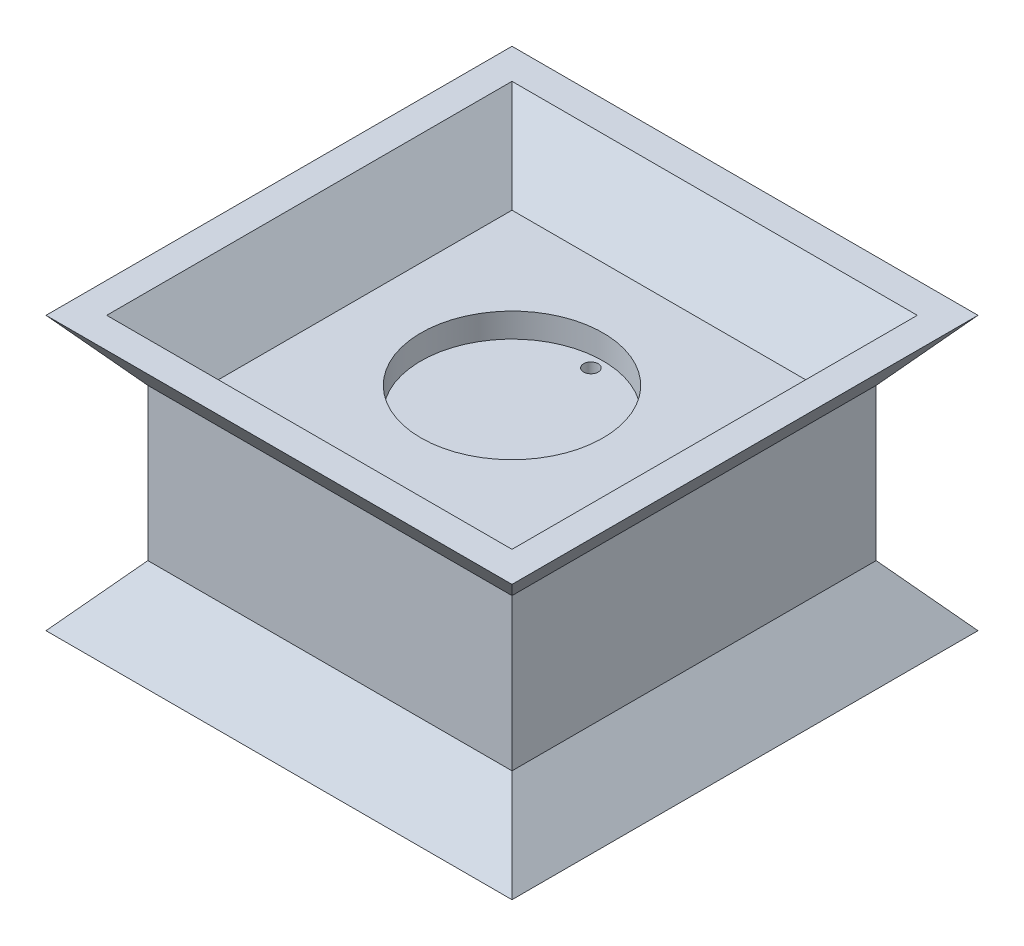
SolidWorks part; units mm, degrees
ref_plane "Front Plane" through (0, 0, 0) normal (0, 0, 1) x (1, 0, 0)
ref_plane "Top Plane" through (0, 0, 0) normal (0, 1, 0) x (1, 0, 0)
ref_plane "Right Plane" through (0, 0, 0) normal (1, 0, 0) x (0, 0, -1)
sketch "Sketch1" plane through (0, 0, 0) normal (0, 1, 0) x (1, 0, 0)
  line L1 (-38.1, -38.1) -> (38.1, -38.1)
  line L2 (-38.1, -38.1) -> (-38.1, 38.1)
  line L3 (-38.1, 38.1) -> (38.1, 38.1)
  line L4 (38.1, -38.1) -> (38.1, 38.1)
  line L5 (-38.1, -38.1) -> (38.1, 38.1) construction
  line L6 (-38.1, 38.1) -> (38.1, -38.1) construction
  point P0 (0, 0)
  dimension "D1" = 76.2
extrude "Boss-Extrude1" add sketch "Sketch1" along normal mid plane 31.75
sketch "Sketch2" plane through (0, 15.875, 0) normal (0, 1, 0) x (1, 0, 0)
  line L0 (-38.1, -38.1) -> (38.1, -38.1) construction
  line L1 (-38.1, 38.1) -> (38.1, 38.1)
  line L2 (-38.1, 38.1) -> (-38.1, -38.1)
  line L3 (-38.1, -38.1) -> (38.1, -38.1)
  line L4 (38.1, 38.1) -> (38.1, -38.1)
extrude "Boss-Extrude2" add sketch "Sketch2" along normal blind 12.7 draft 40 draft outward yes
mirror "Mirror1" about plane through (0, 0, 0) normal (0, 1, 0) of "Boss-Extrude2"
sketch "Sketch4" plane through (0, 28.575, 0) normal (0, 1, 0) x (1, 0, 0)
  line L0 (-42.4066, 25.4201) -> (-48.7566, 25.4201) construction
  line L1 (42.4066, -42.4066) -> (-42.4066, -42.4066)
  line L2 (42.4066, -42.4066) -> (42.4066, 42.4066)
  line L3 (42.4066, 42.4066) -> (-42.4066, 42.4066)
  line L4 (-42.4066, -42.4066) -> (-42.4066, 42.4066)
  line L5 (42.4066, -42.4066) -> (-42.4066, 42.4066) construction
  line L6 (42.4066, 42.4066) -> (-42.4066, -42.4066) construction
  line L7 (-48.7566, 48.7566) -> (-48.7566, -48.7566) construction
  point P0 (0, 0)
  dimension "D1" = 6.35
extrude "Cut-Extrude2" cut sketch "Sketch4" against normal blind 12.7 draft 40
sketch "Sketch5" plane through (0, 15.875, 0) normal (0, 1, 0) x (1, 0, 0)
  circle A0 centre (0, 0) radius 19.05
  dimension "D1" = 38.1
extrude "Cut-Extrude3" cut sketch "Sketch5" against normal blind 5.08
sketch "Sketch6" plane through (0, 10.795, 0) normal (0, 1, 0) x (1, 0, 0)
  line L1 (0, 19.05) -> (0, 13.97) construction
  line L2 (0, 13.97) -> (0, 19.05) construction
  circle A0 centre (0, 0) radius 19.05 construction
  circle A2 centre (0, 16.51) radius 1.524
  dimension "D2" = 3.048
  dimension "D1" = 5.08
extrude "Cut-Extrude4" cut sketch "Sketch6" against normal blind 20.32 contours A2
